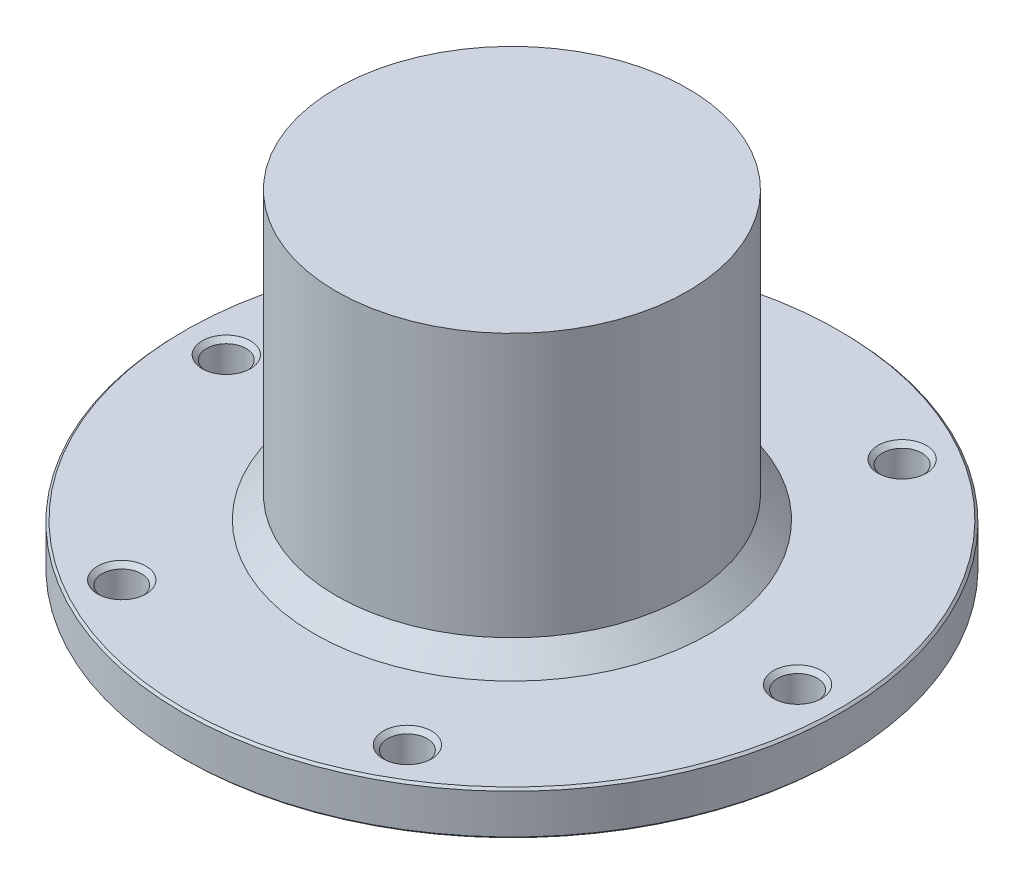
SolidWorks part; units mm, degrees
material "6061-T6 (SS)"
ref_plane "Ebene vorne" through (0, 0, 0) normal (0, 0, 1) x (1, 0, 0)
ref_plane "Ebene oben" through (0, 0, 0) normal (0, 1, 0) x (1, 0, 0)
ref_plane "Ebene rechts" through (0, 0, 0) normal (1, 0, 0) x (0, 0, -1)
sketch "Skizze1" plane through (0, 0, 0) normal (0, 1, 0) x (1, 0, 0)
  line L0 (0, 0) -> (130, 0) construction
  circle A0 centre (0, 0) radius 150
  circle A2 centre (130, 0) radius 9
  circle A3 centre (65, -112.5833) radius 9
  circle A4 centre (-65, -112.5833) radius 9
  circle A5 centre (-130, 0) radius 9
  circle A6 centre (-65, 112.5833) radius 9
  circle A7 centre (65, 112.5833) radius 9
  point P17 (0, 0)
  dimension "D1" = 300
  dimension "D3" = 18
  dimension "D2" = 130
  dimension "D4" = 6
extrude "Aufsatz-Linear austragen1" add sketch "Skizze1" along normal blind 20
sketch "Skizze3" plane through (0, 20, 0) normal (0, 1, 0) x (1, 0, 0)
  circle A0 centre (0, 0) radius 80
  dimension "D1" = 160
extrude "Aufsatz-Linear austragen2" add sketch "Skizze3" along normal blind 130
chamfer "Fase1" distance 1 angle 45 2 edges at (0, 0, 150) (0, 20, 150)
chamfer "Fase2" distance 10 angle 45 1 edges at (0, 20, 80)
chamfer "Fase3" distance 2 angle 45 12 edges at (-65, 0, -103.5833) (-65, 20, -103.5833) (65, 0, -103.5833) (65, 20, -103.5833) (130, 0, 9) (130, 20, 9) (65, 0, 121.5833) (65, 20, 121.5833) (-65, 0, 121.5833) (-65, 20, 121.5833) (-130, 0, 9) (-130, 20, 9)
